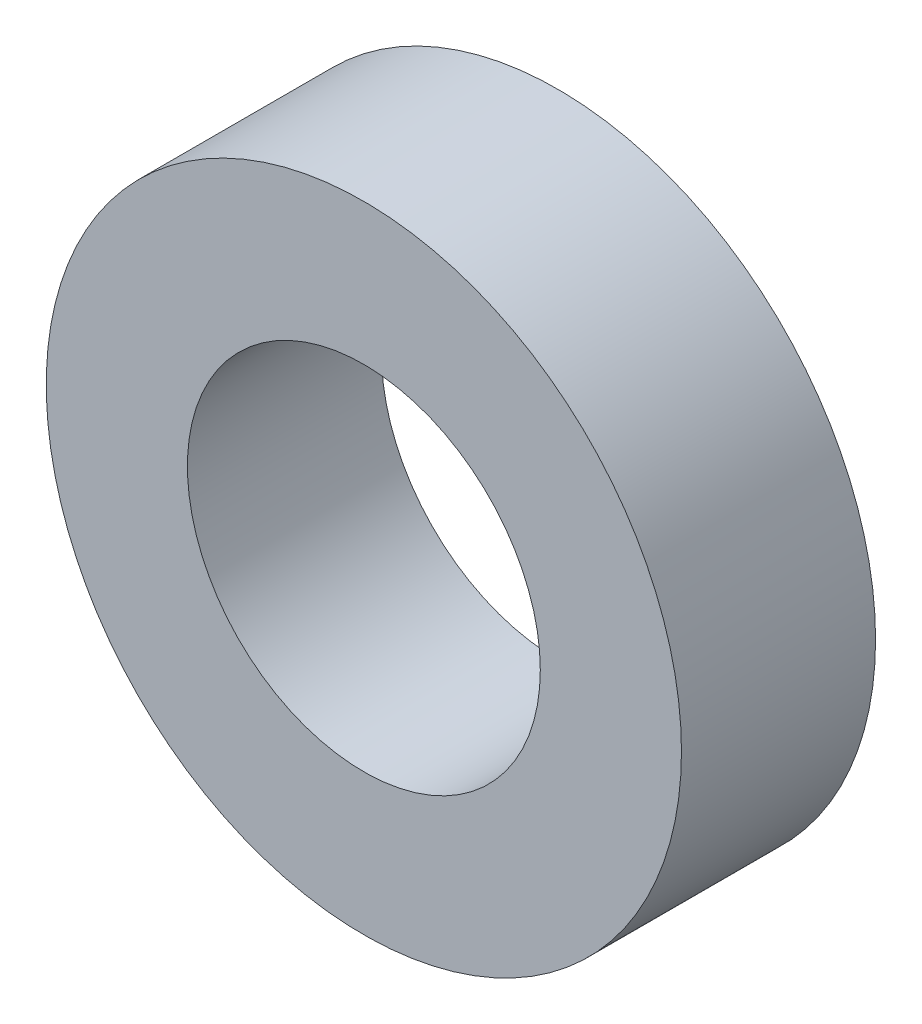
SolidWorks part; units mm, degrees
ref_plane "前视基准面" through (0, 0, 0) normal (0, 0, 1) x (1, 0, 0)
ref_plane "上视基准面" through (0, 0, 0) normal (0, 1, 0) x (1, 0, 0)
ref_plane "右视基准面" through (0, 0, 0) normal (1, 0, 0) x (0, 0, -1)
sketch "草图1" plane through (0, 0, 0) normal (0, 0, 1) x (1, 0, 0)
  circle A0 centre (0, 0) radius 5
  circle A1 centre (0, 0) radius 9
  dimension "D1" = 10
  dimension "D2" = 18
extrude "凸台-拉伸1" add sketch "草图1" along normal mid plane 5.5
